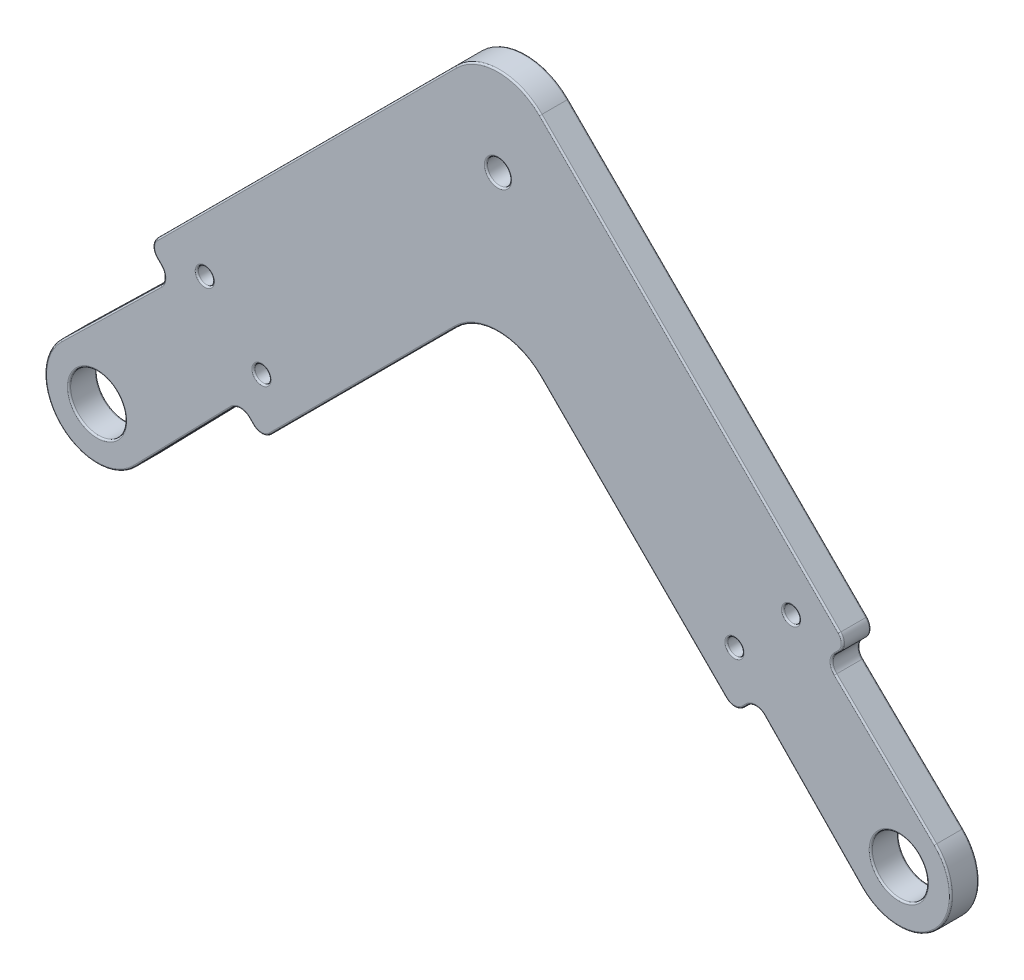
SolidWorks part; units mm, degrees
ref_plane "Front Plane" through (0, 0, 0) normal (0, 0, 1) x (1, 0, 0)
ref_plane "Top Plane" through (0, 0, 0) normal (0, 1, 0) x (1, 0, 0)
ref_plane "Right Plane" through (0, 0, 0) normal (1, 0, 0) x (0, 0, -1)
sketch "Sketch1" plane through (0, 0, 0) normal (0, 0, 1) x (1, 0, 0)
  line L0 (100, 0) -> (-100, 0) construction
  line L1 (-100, 0) -> (0, 100) construction
  line L2 (0, 100) -> (100, 0) construction
  line L3 (0, 0) -> (-50, 50) construction
  line L4 (-40, 60) -> (40, 60) construction
  line L5 (0, 100) -> (0, 60) construction
  circle A0 centre (-100, 0) radius 20
  circle A1 centre (0, 0) radius 20
  circle A2 centre (100, 0) radius 20
  point P2 (0, 0)
  dimension "D5" = 40
  dimension "D1" = 200
  dimension "D2" = 90
  dimension "D3" = 90
  dimension "D4" = 80
sketch "Sketch2" plane through (0, 0, 0) normal (0, 0, 1) x (1, 0, 0)
  line L0 (93.636, 20.5061) -> (79.4939, 6.364)
  line L1 (-56.5165, 43.4835) -> (-40, 60) construction
  line L2 (-100, 0) -> (0, 100) construction
  line L3 (-40, 60) -> (40, 60) construction
  line L4 (40, 60) -> (86.565, 13.435) construction
  line L5 (0, 100) -> (100, 0) construction
  line L6 (-49.4454, 36.4124) -> (-35.8579, 50)
  line L7 (-35.8579, 50) -> (35.8579, 50)
  line L8 (35.8579, 50) -> (79.4939, 6.364)
  line L9 (-63.5876, 50.5546) -> (-44.1421, 70)
  line L10 (-44.1421, 70) -> (44.1421, 70)
  line L11 (44.1421, 70) -> (93.636, 20.5061)
  line L12 (-63.5876, 50.5546) -> (-49.4454, 36.4124)
  line L13 (82.1491, 9.0191) -> (95.3424, -4.534)
  line L14 (90.9809, 17.8509) -> (104.534, 4.6576)
  line L15 (90.1005, 24.0416) -> (75.9584, 9.8995) construction
  line L17 (6, 70) -> (3.4532, 85.4203)
  line L18 (-6, 70) -> (-3.4532, 85.4203)
  line L19 (0, 100) -> (0, 60) construction
  circle A0 centre (100, 0) radius 3.5
  circle A1 centre (100, 0) radius 10 construction
  arc A2 (95.3424, -4.534) -> (104.534, 4.6576) centre (100, 0) ccw
  circle A3 centre (100, 0) radius 20 construction
  circle A4 centre (86.565, 20.5061) radius 1
  circle A5 centre (100, 0) radius 6.5 construction
  circle A6 centre (79.4939, 13.435) radius 1
  circle A7 centre (0, 60) radius 1.5
  circle A8 centre (0, 84.85) radius 1.5
  arc A9 (3.4532, 85.4203) -> (-3.4532, 85.4203) centre (0, 84.85) ccw
  circle A10 centre (-50, 50) radius 1.5
  circle A11 centre (0, 84.85) radius 3.5 construction
  point P32 (106.5, 0)
  point P52 (3.5, 82)
  dimension "D4" = 20
  dimension "D5" = 7
  dimension "D9" = 2
  dimension "D12" = 3
  dimension "D17" = 3
  dimension "D3" = 27.5
  dimension "D7" = 19
  dimension "D8" = 5
  dimension "D10" = 5
  dimension "D11" = 5
  dimension "D13" = 14.85
  dimension "D15" = 6
  dimension "D16" = 6
  dimension "D1" = 10
  dimension "D2" = 10
  dimension "D6" = 3
  dimension "D14" = 2
sketch "Sketch3" plane through (0, 0, 0) normal (0, 0, 1) x (1, 0, 0)
  line L0 (-86.565, 13.435) -> (-50, 50) construction
  line L1 (-100, 0) -> (0, 100) construction
  line L2 (-50, 50) -> (-13.435, 13.435) construction
  line L3 (0, 0) -> (-50, 50) construction
  line L4 (-79.4939, 6.364) -> (-50, 35.8579)
  line L5 (-50, 35.8579) -> (-20.5061, 6.364)
  line L6 (-93.636, 20.5061) -> (-50, 64.1421)
  line L7 (-50, 64.1421) -> (-6.364, 20.5061)
  line L8 (-79.4939, 6.364) -> (-50, 35.8579) construction
  line L9 (-93.636, 20.5061) -> (-50, 64.1421) construction
  line L10 (-93.636, 20.5061) -> (-79.4939, 6.364)
  line L11 (-6.364, 20.5061) -> (-20.5061, 6.364)
  line L12 (-104.534, 4.6576) -> (-90.9809, 17.8509)
  line L13 (-82.1491, 9.0191) -> (-95.3424, -4.534)
  line L14 (-17.8509, 9.0191) -> (-4.6576, -4.534)
  line L15 (-9.0191, 17.8509) -> (4.534, 4.6576)
  line L16 (-9.8995, 24.0416) -> (-24.0416, 9.8995) construction
  line L17 (-90.1005, 24.0416) -> (-75.9584, 9.8995) construction
  circle A0 centre (-100, 0) radius 3.5
  circle A1 centre (-100, 0) radius 10 construction
  circle A2 centre (0, 0) radius 3.5
  circle A3 centre (0, 0) radius 10 construction
  arc A4 (-104.534, 4.6576) -> (-95.3424, -4.534) centre (-100, 0) ccw
  arc A5 (-4.6576, -4.534) -> (4.534, 4.6576) centre (0, 0) ccw
  circle A6 centre (-100, 0) radius 20 construction
  circle A7 centre (0, 0) radius 20 construction
  circle A8 centre (-86.565, 20.5061) radius 1
  circle A9 centre (-100, 0) radius 6.5 construction
  circle A10 centre (0, 0) radius 6.5 construction
  circle A11 centre (-79.4939, 13.435) radius 1
  circle A12 centre (-20.5061, 13.435) radius 1
  circle A13 centre (-13.435, 20.5061) radius 1
  circle A14 centre (-50, 50) radius 1.5 construction
  circle A15 centre (-50, 50) radius 1.5
  point P9 (6.5, 0)
  point P43 (-93.5, 0)
  dimension "D1" = 20
  dimension "D2" = 7
  dimension "D8" = 2
  dimension "D6" = 19
  dimension "D7" = 19
  dimension "D9" = 5
  dimension "D10" = 5
  dimension "D11" = 5
  dimension "D12" = 5
  dimension "D13" = 5
  dimension "D14" = 5
  dimension "D3" = 3
  dimension "D4" = 10
  dimension "D5" = 10
sketch "Sketch4" plane through (0, 0, 0) normal (0, 0, 1) x (1, 0, 0)
  line L0 (-57.5062, 93.35) -> (57.4938, 93.35)
  line L1 (57.4938, 93.35) -> (57.4938, 83.35)
  line L2 (57.4938, 83.35) -> (44.1421, 70)
  line L3 (44.1421, 70) -> (-44.1421, 70)
  line L4 (-44.1421, 70) -> (-57.5062, 83.35)
  line L5 (-57.5062, 83.35) -> (-57.5062, 93.35)
  line L6 (4, 60) -> (4, 70)
  line L7 (-4, 60) -> (-4, 70)
  line L8 (-22.5, 84.85) -> (22.5, 84.85) construction
  line L9 (-22.5, 89.35) -> (22.5, 89.35)
  line L10 (-22.5, 80.35) -> (22.5, 80.35)
  circle A0 centre (0, 60) radius 1.5 construction
  circle A1 centre (0, 60) radius 1.5
  arc A2 (-4, 60) -> (4, 60) centre (0, 60) ccw
  arc A3 (-22.5, 89.35) -> (-22.5, 80.35) centre (-22.5, 84.85) ccw
  circle A4 centre (0, 60) radius 4 construction
  arc A5 (22.5, 80.35) -> (22.5, 89.35) centre (22.5, 84.85) ccw
  point P20 (4, 60)
  point P23 (0, 84.85)
  dimension "D5" = 9
  dimension "D1" = 115
  dimension "D2" = 10
  dimension "D4" = 45
  dimension "D6" = 4
  dimension "D3" = 2.5
sketch "Sketch5" plane through (0, 0, 0) normal (0, 0, 1) x (1, 0, 0)
  line L0 (-82.1491, 9.0191) -> (-95.3424, -4.534) construction
  line L1 (-104.534, 4.6576) -> (-90.9809, 17.8509) construction
  line L2 (-17.8509, 9.0191) -> (-4.6576, -4.534) construction
  line L3 (-9.0191, 17.8509) -> (4.534, 4.6576) construction
  line L4 (-82.1491, 9.0191) -> (-95.3424, -4.534)
  line L5 (-104.534, 4.6576) -> (-90.9809, 17.8509)
  line L6 (-79.4939, 6.364) -> (-50, 35.8579)
  line L7 (-50, 35.8579) -> (-20.5061, 6.364)
  line L8 (-20.5061, 6.364) -> (-6.364, 20.5061)
  line L9 (-6.364, 20.5061) -> (-50, 64.1421)
  line L10 (-50, 64.1421) -> (-93.636, 20.5061)
  line L11 (-93.636, 20.5061) -> (-79.4939, 6.364)
  line L12 (-79.4939, 6.364) -> (-50, 35.8579)
  line L13 (-50, 35.8579) -> (-20.5061, 6.364)
  line L14 (-20.5061, 6.364) -> (-17.8509, 9.0191)
  line L15 (-6.364, 20.5061) -> (-50, 64.1421)
  line L16 (-50, 64.1421) -> (-93.636, 20.5061)
  line L17 (-93.636, 20.5061) -> (-90.9809, 17.8509)
  line L18 (-17.8509, 9.0191) -> (-4.6576, -4.534)
  line L19 (-9.0191, 17.8509) -> (4.534, 4.6576)
  line L20 (-82.1491, 9.0191) -> (-79.4939, 6.364)
  line L21 (-9.0191, 17.8509) -> (-6.364, 20.5061)
  arc A0 (-104.534, 4.6576) -> (-95.3424, -4.534) centre (-100, 0) ccw construction
  circle A1 centre (0, 0) radius 3.5
  circle A2 centre (0, 0) radius 3.5
  circle A3 centre (-100, 0) radius 3.5
  circle A4 centre (-100, 0) radius 3.5
  circle A5 centre (-86.565, 20.5061) radius 1
  circle A6 centre (-86.565, 20.5061) radius 1
  circle A7 centre (-50, 50) radius 1.5
  circle A8 centre (-50, 50) radius 1.5
  circle A9 centre (-13.435, 20.5061) radius 1
  circle A10 centre (-13.435, 20.5061) radius 1
  circle A11 centre (-20.5061, 13.435) radius 1
  circle A12 centre (-20.5061, 13.435) radius 1
  circle A13 centre (-79.4939, 13.435) radius 1
  circle A14 centre (-79.4939, 13.435) radius 1
  arc A15 (-4.6576, -4.534) -> (4.534, 4.6576) centre (0, 0) ccw construction
  arc A16 (-104.534, 4.6576) -> (-95.3424, -4.534) centre (-100, 0) ccw
  arc A17 (-4.6576, -4.534) -> (4.534, 4.6576) centre (0, 0) ccw
  dimension "D1" = 0
  dimension "D2" = 0
  dimension "D3" = 0
  dimension "D4" = 0
  dimension "D5" = 0
  dimension "D6" = 0
  dimension "D7" = 0
  dimension "D8" = 0
extrude "Boss-Extrude1" add sketch "Sketch5" along normal blind 3.5
fillet "Fillet1" radius 7.5 2 edges at (-50, 35.8579, 1.75) (-50, 64.1421, 1.75)
fillet "Fillet2" radius 1.5 8 edges at (-90.9809, 17.8509, 1.75) (-93.636, 20.5061, 1.75) (-79.4939, 6.364, 1.75) (-82.1491, 9.0191, 1.75) (-6.364, 20.5061, 1.75) (-9.0191, 17.8509, 1.75) (-17.8509, 9.0191, 1.75) (-20.5061, 6.364, 1.75)
fillet "Fillet3" radius 0.2 62 edges at (-78.4939, 13.435, 0) (-78.4939, 13.435, 3.5) (-19.5061, 13.435, 0) (-19.5061, 13.435, 3.5) (-12.435, 20.5061, 0) (-12.435, 20.5061, 3.5) (-48.5, 50, 0) (-48.5, 50, 3.5) (-85.565, 20.5061, 0) (-85.565, 20.5061, 3.5) (-96.5, 0, 0) (-96.5, 0, 3.5) (3.5, 0, 0) (3.5, 0, 3.5) (-80.8143, 7.6844, 0) (-66.8683, 18.9896, 0) (-33.1317, 18.9896, 0) (-19.1857, 7.6844, 0) (-10.724, 1.6979, 0) (4.5962, -4.5962, 0) (-1.6979, 10.724, 0) (-7.6844, 19.1857, 0) (-26.0607, 40.2028, 0) (-73.9393, 40.2028, 0) (-92.3156, 19.1857, 0) (-98.3021, 10.724, 0) (-104.5962, -4.5962, 0) (-89.276, 1.6979, 0) (-80.8143, 7.6844, 3.5) (-66.8683, 18.9896, 3.5) (-33.1317, 18.9896, 3.5) (-19.1857, 7.6844, 3.5) (-10.724, 1.6979, 3.5) (4.5962, -4.5962, 3.5) (-1.6979, 10.724, 3.5) (-7.6844, 19.1857, 3.5) (-73.9393, 40.2028, 3.5) (-92.3156, 19.1857, 3.5) (-98.3021, 10.724, 3.5) (-104.5962, -4.5962, 3.5) (-89.276, 1.6979, 3.5) (-50, 61.0355, 0) (-50, 61.0355, 3.5) (-50, 32.7513, 0) (-50, 32.7513, 3.5) (-20.5061, 6.9853, 0) (-6.9853, 20.5061, 0) (-79.4939, 6.9853, 0) (-93.0147, 20.5061, 0) (-20.5061, 6.9853, 3.5) (-6.9853, 20.5061, 3.5) (-79.4939, 6.9853, 3.5) (-93.0147, 20.5061, 3.5) (-91.6166, 17.8552, 0) (-91.6166, 17.8552, 3.5) (-82.1448, 8.3834, 0) (-82.1448, 8.3834, 3.5) (-8.3834, 17.8552, 0) (-8.3834, 17.8552, 3.5) (-17.8552, 8.3834, 0) (-17.8552, 8.3834, 3.5) (-26.0607, 40.2028, 3.5)
